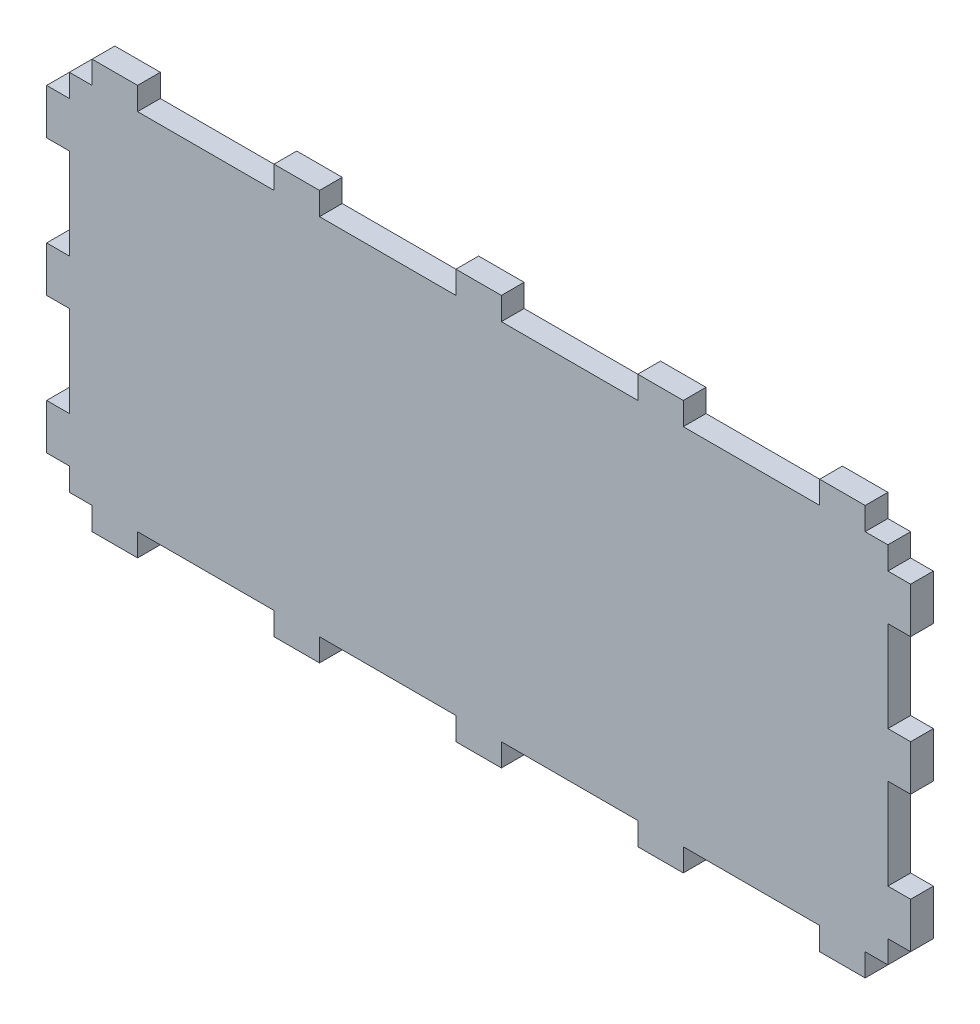
SolidWorks part; units mm, degrees
ref_plane "Ön Düzlem" through (0, 0, 0) normal (0, 0, 1) x (1, 0, 0)
ref_plane "Üst Düzlem" through (0, 0, 0) normal (0, 1, 0) x (1, 0, 0)
ref_plane "Sağ Düzlem" through (0, 0, 0) normal (1, 0, 0) x (0, 0, -1)
sketch "Sketch1" plane through (0, 0, 0) normal (0, 0, 1) x (1, 0, 0)
  line L0 (-85, 40) -> (-85, 45)
  line L1 (-90, -40) -> (-85, -40)
  line L2 (-90, -40) -> (-90, -35)
  line L3 (-90, 40) -> (-85, 40)
  line L4 (90, -40) -> (90, -35)
  line L5 (-90, -40) -> (90, 40) construction
  line L6 (-90, 40) -> (90, -40) construction
  line L7 (-85, 45) -> (-75, 45)
  line L8 (-75, 45) -> (-75, 40)
  line L9 (-45, 40) -> (-45, 45)
  line L10 (-35, 45) -> (-35, 40)
  line L11 (-45, 45) -> (-35, 45)
  line L12 (-5, 40) -> (-5, 45)
  line L13 (5, 45) -> (5, 40)
  line L14 (-5, 45) -> (5, 45)
  line L15 (35, 40) -> (35, 45)
  line L16 (45, 45) -> (45, 40)
  line L17 (35, 45) -> (45, 45)
  line L18 (75, 40) -> (75, 45)
  line L19 (85, 45) -> (85, 40)
  line L20 (75, 45) -> (85, 45)
  line L21 (-75, 40) -> (-45, 40)
  line L22 (-35, 40) -> (-5, 40)
  line L23 (5, 40) -> (35, 40)
  line L24 (45, 40) -> (75, 40)
  line L25 (85, 40) -> (90, 40)
  line L26 (-95, 0) -> (95, 0) construction
  line L27 (0, -40) -> (0, 40) construction
  line L28 (-90, 35) -> (-95, 35)
  line L29 (-95, 35) -> (-95, 25)
  line L30 (-95, 25) -> (-90, 25)
  line L31 (-95, -5) -> (-90, -5)
  line L32 (-90, 5) -> (-95, 5)
  line L33 (-95, 5) -> (-95, -5)
  line L34 (-95, -35) -> (-90, -35)
  line L35 (-90, -25) -> (-95, -25)
  line L36 (-95, -25) -> (-95, -35)
  line L37 (95, 25) -> (90, 25)
  line L38 (90, 35) -> (95, 35)
  line L39 (95, 35) -> (95, 25)
  line L40 (90, 5) -> (95, 5)
  line L41 (95, 5) -> (95, -5)
  line L42 (95, -5) -> (90, -5)
  line L43 (90, -25) -> (95, -25)
  line L44 (95, -25) -> (95, -35)
  line L45 (95, -35) -> (90, -35)
  line L46 (85, -45) -> (85, -40)
  line L47 (75, -45) -> (85, -45)
  line L48 (75, -40) -> (75, -45)
  line L49 (45, -45) -> (45, -40)
  line L50 (35, -45) -> (45, -45)
  line L51 (35, -40) -> (35, -45)
  line L52 (5, -45) -> (5, -40)
  line L53 (-5, -45) -> (5, -45)
  line L55 (-35, -45) -> (-35, -40)
  line L56 (-45, -45) -> (-35, -45)
  line L57 (-45, -40) -> (-45, -45)
  line L58 (-75, -45) -> (-75, -40)
  line L59 (-85, -45) -> (-75, -45)
  line L60 (-85, -40) -> (-85, -45)
  line L61 (-75, -40) -> (-45, -40)
  line L63 (5, -40) -> (35, -40)
  line L64 (45, -40) -> (75, -40)
  line L65 (85, -40) -> (90, -40)
  line L66 (-90, -25) -> (-90, -5)
  line L67 (-90, 5) -> (-90, 25)
  line L68 (-90, 35) -> (-90, 40)
  line L69 (90, 35) -> (90, 40)
  line L70 (90, 5) -> (90, 25)
  line L71 (90, -25) -> (90, -5)
  line L72 (-35, -40) -> (-5, -40)
  line L73 (-5, -40) -> (-5, -45)
  point P0 (0, 0)
  dimension "D1" = 80
  dimension "D2" = 180
  dimension "D7" = 10
  dimension "D8" = 5
  dimension "D9" = 5
  dimension "D11" = 30
  dimension "D12" = 5
  dimension "D13" = 10
  dimension "D14" = 5
  dimension "D16" = 30
  dimension "D17" = 20
  dimension "D18" = 30
  dimension "D10" = 5
  dimension "D15" = 3
extrude "Boss-Extrude1" add sketch "Sketch1" along normal blind 5
